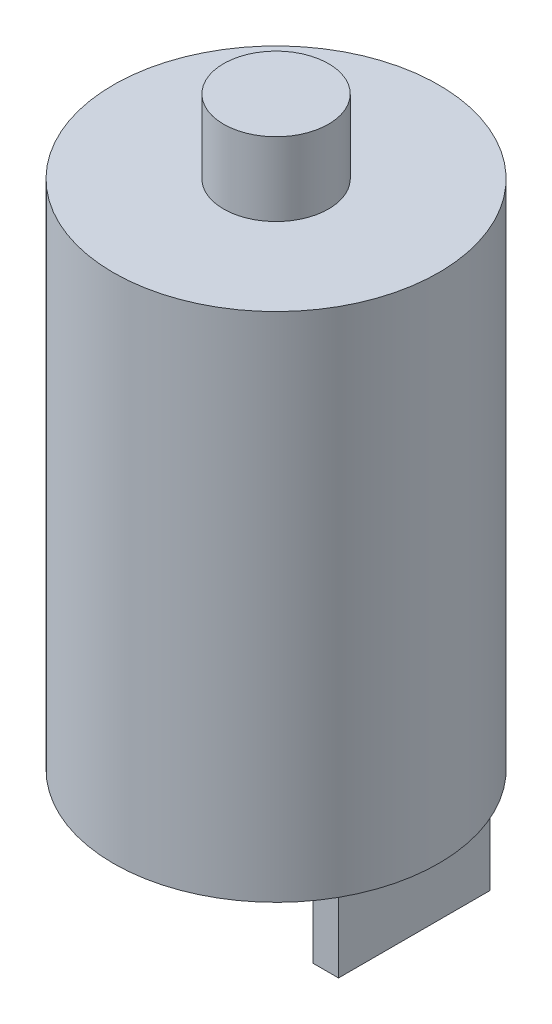
SolidWorks part; units mm, degrees
ref_plane "Front Plane" through (0, 0, 0) normal (0, 0, 1) x (1, 0, 0)
ref_plane "Top Plane" through (0, 0, 0) normal (0, 1, 0) x (1, 0, 0)
ref_plane "Right Plane" through (0, 0, 0) normal (1, 0, 0) x (0, 0, -1)
sketch "Sketch1" plane through (0, 0, 0) normal (0, 1, 0) x (1, 0, 0)
  circle A0 centre (0, 0) radius 6.2
  dimension "D1" = 12.4
extrude "Boss-Extrude1" add sketch "Sketch1" along normal blind 19.5
sketch "Sketch2" plane through (0, 19.5, 0) normal (0, 1, 0) x (1, 0, 0)
  circle A0 centre (0, 0) radius 2
  dimension "D1" = 4
extrude "Boss-Extrude2" add sketch "Sketch2" along normal blind 2.8
sketch "Sketch3" plane through (0, 0, 0) normal (0, -1, 0) x (1, 0, 0)
  line L0 (0, 0) -> (-1.7541, 0) construction
  line L1 (4.3072, 2.8899) -> (5.2705, 2.8899)
  line L2 (4.3072, 2.8899) -> (4.3072, -2.8899)
  line L3 (4.3072, -2.8899) -> (5.2705, -2.8899)
  line L4 (5.2705, 2.8899) -> (5.2705, -2.8899)
  line L5 (0, 0) -> (0, 2.0481) construction
  line L6 (-4.3072, -2.8899) -> (-5.2705, -2.8899)
  line L7 (-4.3072, 2.8899) -> (-5.2705, 2.8899)
  line L8 (-4.3072, 2.8899) -> (-4.3072, -2.8899)
  line L9 (-5.2705, 2.8899) -> (-5.2705, -2.8899)
  circle A0 centre (0, 0) radius 6.2 construction
  dimension "D1" = 5.7798
  dimension "D3" = 0.9633
  dimension "D2" = 5.2705
extrude "Boss-Extrude3" add sketch "Sketch3" along normal blind 2.8
equation "\"D2@Sketch3\"=(0.485in-0.07in)/2"
